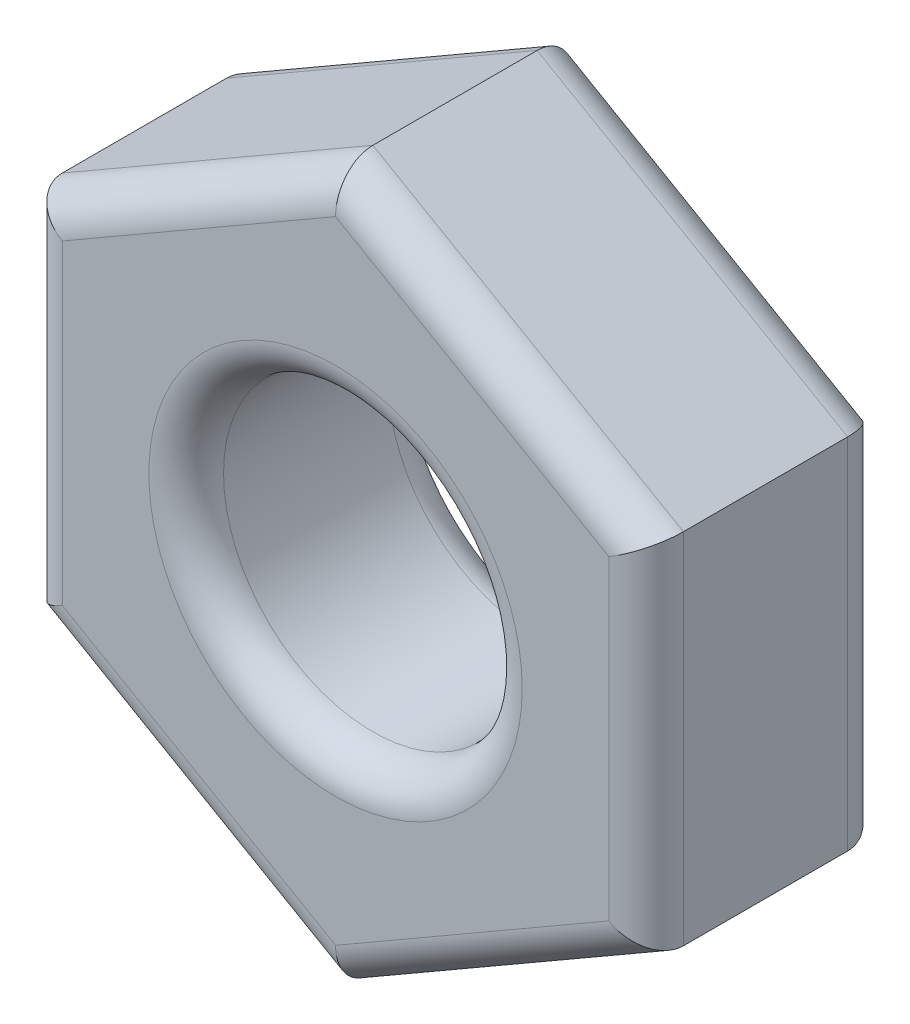
SolidWorks part; units mm, degrees
ref_plane "Front Plane" through (0, 0, 0) normal (0, 0, 1) x (1, 0, 0)
ref_plane "Top Plane" through (0, 0, 0) normal (0, 1, 0) x (1, 0, 0)
ref_plane "Right Plane" through (0, 0, 0) normal (1, 0, 0) x (0, 0, -1)
sketch "Sketch1" plane through (0, 0, 0) normal (0, 0, 1) x (1, 0, 0)
  line L1 (2.08, -1.2009) -> (2.08, 1.2009)
  line L2 (2.08, 1.2009) -> (0, 2.4018)
  line L3 (0, 2.4018) -> (-2.08, 1.2009)
  line L4 (-2.08, 1.2009) -> (-2.08, -1.2009)
  line L5 (-2.08, -1.2009) -> (0, -2.4018)
  line L6 (0, -2.4018) -> (2.08, -1.2009)
  circle A0 centre (0, 0) radius 1
  circle A1 centre (0, 0) radius 2.08 construction
  dimension "D1" = 2
  dimension "D2" = 4.16
extrude "Boss-Extrude1" add sketch "Sketch1" along normal mid plane 1.6
fillet "Fillet1" radius 0.25 14 edges at (1, 0, 0.8) (-1.04, -1.8013, 0.8) (-2.08, 0, 0.8) (-1.04, 1.8013, 0.8) (1.04, 1.8013, 0.8) (2.08, 0, 0.8) (1.04, -1.8013, 0.8) (1, 0, -0.8) (2.08, 0, -0.8) (1.04, 1.8013, -0.8) (-1.04, 1.8013, -0.8) (-2.08, 0, -0.8) (-1.04, -1.8013, -0.8) (1.04, -1.8013, -0.8)
